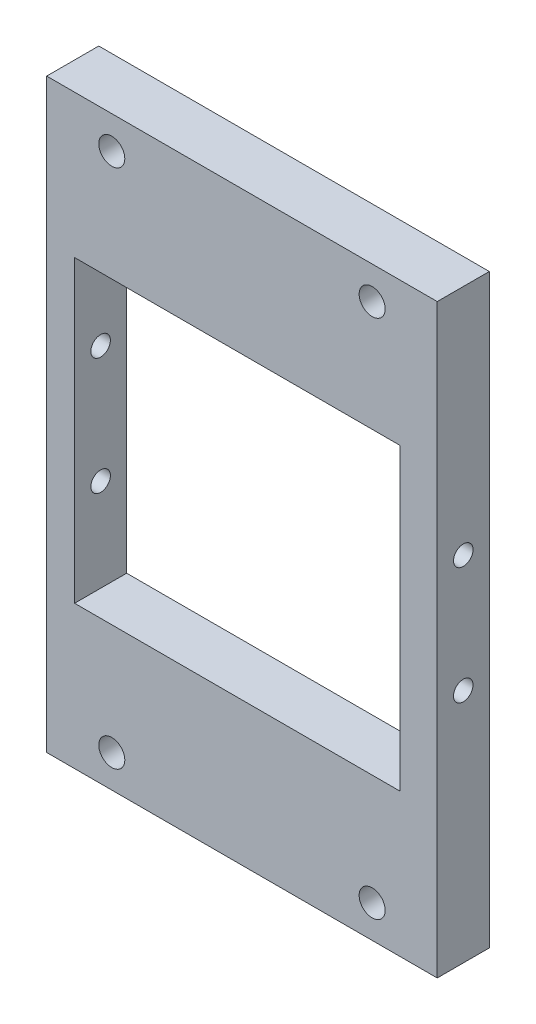
SolidWorks part; units mm, degrees
ref_plane "Front" through (0, 0, 0) normal (0, 0, 1) x (1, 0, 0)
ref_plane "Top" through (0, 0, 0) normal (0, 1, 0) x (1, 0, 0)
ref_plane "Right" through (0, 0, 0) normal (1, 0, 0) x (0, 0, -1)
sketch "草图1" plane through (0, 0, 0) normal (0, 0, 1) x (1, 0, 0)
  line L1 (-25.2871, -45) -> (-85.2871, -45)
  line L2 (-25.2871, -45) -> (-25.2871, 45)
  line L3 (-25.2871, 45) -> (-85.2871, 45)
  line L4 (-85.2871, -45) -> (-85.2871, 45)
  line L5 (-25.2871, -45) -> (-85.2871, 45) construction
  line L6 (-25.2871, 45) -> (-85.2871, -45) construction
  point P0 (-55.2871, 0)
  dimension "D1" = 60
  dimension "D2" = 90
extrude "凸台-拉伸1" add sketch "草图1" along normal blind 8 contours L1 L4 L3 L2
sketch "草图2" plane through (0, 0, 8) normal (0, 0, 1) x (1, 0, 0)
  line L0 (-81, 17) -> (-81, 23) construction
  line L1 (-81, 17) -> (-81, -17) construction
  line L2 (-81, -23) -> (-81, -17) construction
  line L3 (-31, -23) -> (-81, -23) construction
  line L4 (-31, -23) -> (-31, -17) construction
  line L5 (-31, 17) -> (-31, -17) construction
  line L6 (-31, 17) -> (-31, 23) construction
  line L7 (-31, 23) -> (-81, 23) construction
  line L8 (-81, 17) -> (-81, 23)
  line L9 (-81, 17) -> (-81, -17)
  line L10 (-81, -23) -> (-81, -17)
  line L11 (-31, -23) -> (-81, -23)
  line L12 (-31, -23) -> (-31, -17)
  line L13 (-31, 17) -> (-31, -17)
  line L14 (-31, 17) -> (-31, 23)
  line L15 (-31, 23) -> (-81, 23)
extrude "切除-拉伸1" cut sketch "草图2" against normal up to surface (8 mm away)
sketch "草图3" plane through (0, 0, 8) normal (0, 0, 1) x (1, 0, 0)
  line L0 (-75.2871, -40) -> (-35.2871, -40) construction
  line L1 (-85.2871, -45) -> (-85.2871, 45) construction
  line L2 (-25.2871, -45) -> (-85.2871, -45) construction
  circle A0 centre (-75.2871, -40) radius 2
  circle A1 centre (-35.2871, -40) radius 2
  dimension "D3" = 4
  dimension "D1" = 10
  dimension "D2" = 40
  dimension "D4" = 5
extrude "切除-拉伸2" cut sketch "草图3" against normal through all
mirror "镜向1" about plane through (0, 0, 0) normal (0, 1, 0) of "切除-拉伸2"
sketch "草图4" plane through (-85.2871, 0, 0) normal (-1, 0, 0) x (0, 0, 1)
  line L0 (8, -45) -> (8, 45) construction
  circle A0 centre (4, -8.7474) radius 1.5
  circle A1 centre (4, 9.2526) radius 1.5
  dimension "D1" = 3
  dimension "D2" = 4
  dimension "D3" = 18
extrude "切除-拉伸3" cut sketch "草图4" against normal through all
